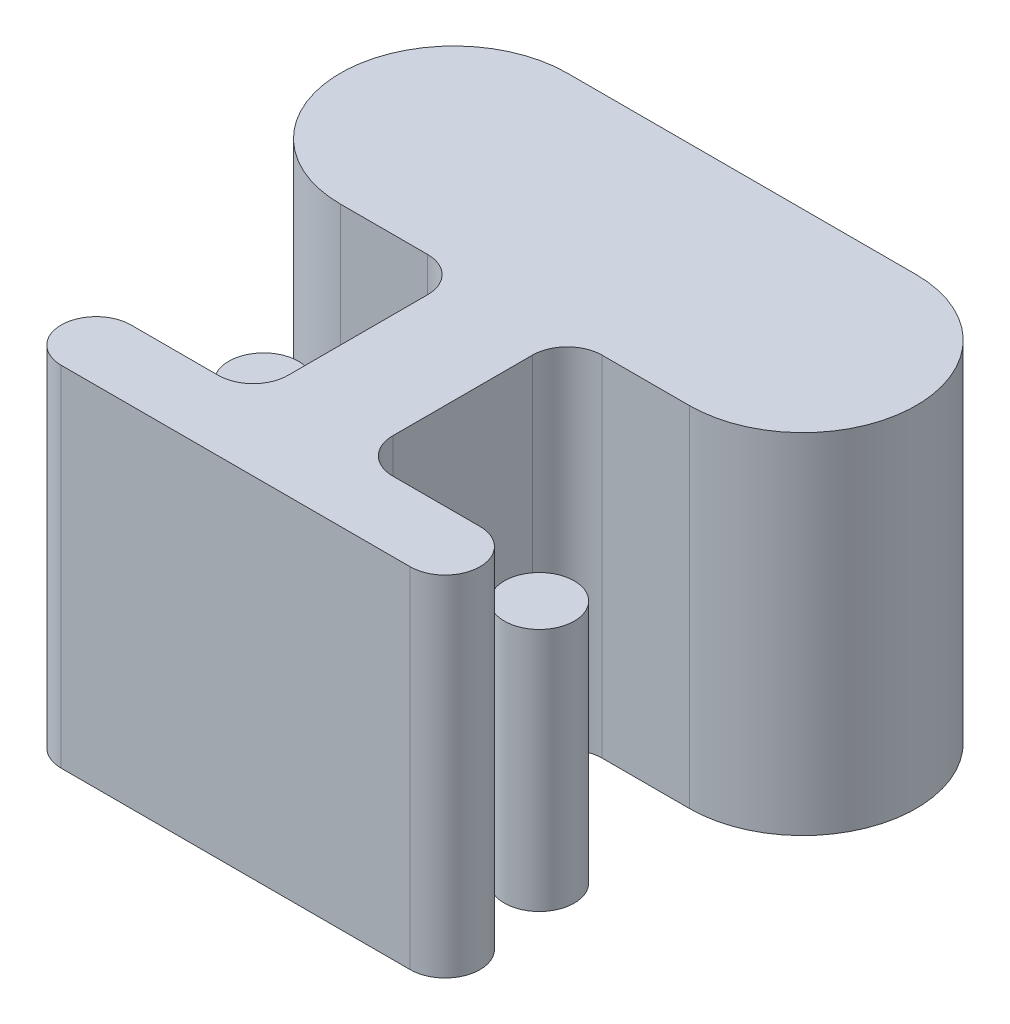
SolidWorks part; units mm, degrees
ref_plane "Front Plane" through (0, 0, 0) normal (0, 0, 1) x (1, 0, 0)
ref_plane "Top Plane" through (0, 0, 0) normal (0, 1, 0) x (1, 0, 0)
ref_plane "Right Plane" through (0, 0, 0) normal (1, 0, 0) x (0, 0, -1)
sketch "Sketch1" plane through (0, 0, 0) normal (0, 1, 0) x (1, 0, 0)
  line L0 (150, -325) -> (500, -325)
  line L1 (-500, -325) -> (-150, -325)
  line L3 (-500, 325) -> (500, 325)
  line L5 (-500, -325) -> (500, 325) construction
  line L6 (-500, 325) -> (500, -325) construction
  line L8 (-150, -925) -> (-150, -325)
  line L10 (150, -925) -> (150, -325)
  line L11 (-150, -925) -> (150, -325) construction
  line L12 (-150, -325) -> (150, -925) construction
  line L13 (-500, -925) -> (-150, -925)
  line L15 (-500, -1125) -> (500, -1125)
  line L17 (150, -925) -> (500, -925)
  line L18 (-150, -325) -> (150, -325) construction
  arc A0 (-500, -325) -> (-500, 325) centre (-500, 0) cw
  arc A1 (500, -325) -> (500, 325) centre (500, 0) ccw
  arc A2 (500, -1125) -> (500, -925) centre (500, -1025) ccw
  arc A3 (-500, -1125) -> (-500, -925) centre (-500, -1025) cw
  point P0 (0, 0)
  point P6 (0, -625)
  point P15 (0, -1125)
  point P16 (0, 325)
  point P19 (0, 0)
  dimension "D1" = 1000
  dimension "D2" = 1000
  dimension "D3" = 600
  dimension "D4" = 300
  dimension "D5" = 650
  dimension "D6" = 200
extrude "Boss-Extrude1" add sketch "Sketch1" along normal blind 1000
fillet "Fillet1" radius 100 4 edges at (150, 500, 925) (-150, 500, 925) (-150, 500, 325) (150, 500, 325)
sketch "Sketch2" plane through (0, 0, 0) normal (0, -1, 0) x (1, 0, 0)
  line L0 (0, 1125) -> (0, -325) construction
  line L1 (-500, 1125) -> (500, 1125) construction
  line L2 (500, -325) -> (-500, -325) construction
  line L3 (500, 925) -> (250, 925) construction
  line L4 (370, 625) -> (570, 625)
  line L5 (370, 625) -> (370, 825)
  line L6 (370, 825) -> (570, 825)
  line L7 (570, 625) -> (570, 825)
  line L8 (370, 625) -> (570, 825) construction
  line L9 (370, 825) -> (570, 625) construction
  line L10 (-500, 325) -> (-250, 325) construction
  line L11 (-470, 475) -> (-470, 675) construction
  line L13 (470, 625) -> (470, 825) construction
  circle A0 centre (470, 725) radius 100
  circle A2 centre (-470, 575) radius 100
  point P0 (470, 725)
  dimension "D1" = 200
  dimension "D2" = 200
  dimension "D3" = 200
  dimension "D4" = 200
  dimension "D5" = 250
  dimension "D6" = 470
  dimension "D7" = 470
extrude "Boss-Extrude2" add sketch "Sketch2" against normal blind 700 separate body contours A0
